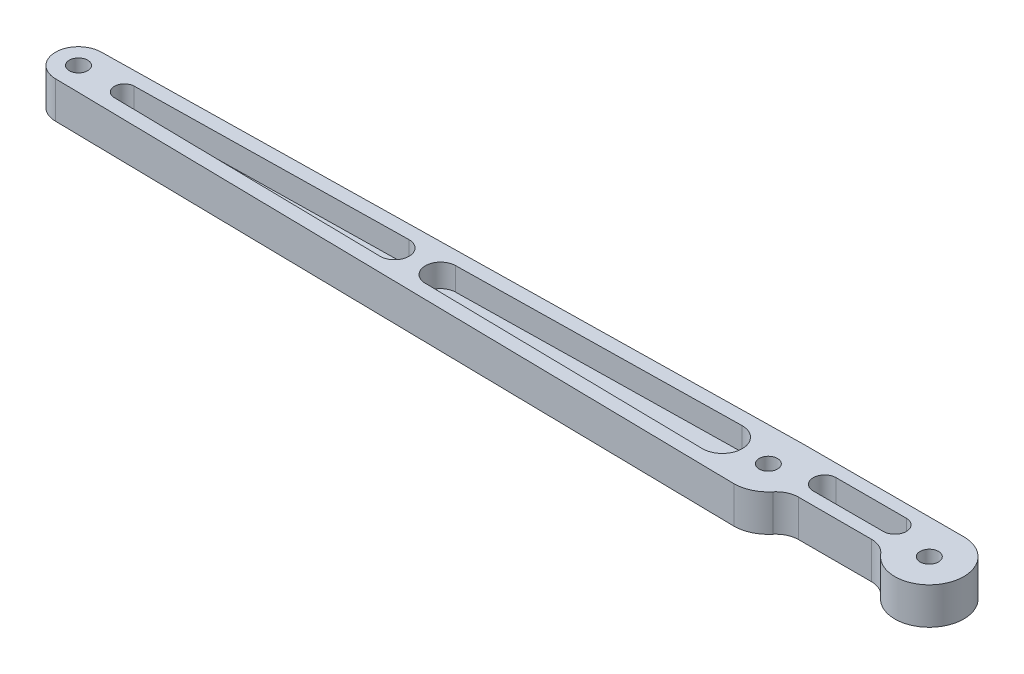
SolidWorks part; units mm, degrees
ref_plane "Front Plane" through (0, 0, 0) normal (0, 0, 1) x (1, 0, 0)
ref_plane "Top Plane" through (0, 0, 0) normal (0, 1, 0) x (1, 0, 0)
ref_plane "Right Plane" through (0, 0, 0) normal (1, 0, 0) x (0, 0, -1)
sketch "Sketch1" plane through (0, 0, 0) normal (0, 1, 0) x (1, 0, 0)
  line L0 (-68.657, 3.6299) -> (-61.657, 3.6299) construction
  line L1 (86.343, 11.1299) -> (121.343, 11.1299)
  line L5 (86.343, 11.1299) -> (86.343, -3.8701) construction
  line L6 (95.9477, 0.6299) -> (111.7383, 0.6299)
  line L7 (93.843, 3.6299) -> (128.843, 3.6299) construction
  line L8 (128.2168, 0.6299) -> (142.8276, 0.6299)
  line L9 (86.343, 11.1299) -> (-63.657, 8.6299)
  line L10 (86.343, -3.8701) -> (-63.657, -1.3701)
  line L11 (84.343, 3.6299) -> (88.343, 3.6299) construction
  circle A0 centre (86.343, 3.6299) radius 2
  circle A1 centre (121.343, 3.6299) radius 2
  arc A2 (121.343, -3.8701) -> (121.343, 11.1299) centre (121.343, 3.6299) ccw
  arc A3 (86.343, -3.8701) -> (92.1058, -1.1701) centre (86.343, 3.6299) ccw
  arc A4 (115.5802, -1.1701) -> (121.343, 11.1299) centre (121.343, 3.6299) ccw
  arc A5 (115.5802, -1.1701) -> (111.7383, 0.6299) centre (111.7383, -4.3701) ccw
  arc A6 (95.9477, 0.6299) -> (92.1058, -1.1701) centre (95.9477, -4.3701) ccw
  circle A7 centre (-63.657, 3.6299) radius 2
  arc A8 (-63.657, 8.6299) -> (-63.657, -1.3701) centre (-63.657, 3.6299) ccw
  dimension "D3" = 4
  dimension "D4" = 4
  dimension "D7" = 5
  dimension "D8" = 4
  dimension "D1" = 3
  dimension "D5" = 7.5
  dimension "D6" = 35
  dimension "D9" = 5
  dimension "D10" = 197.5
extrude "Boss-Extrude1" add sketch "Sketch1" along normal blind 8 contours L9 A8 L10 A3 A6 L6 A5 A4 A2 L1 A0 A1 A7
sketch "Sketch2" plane through (0, 8, 0) normal (0, 1, 0) x (1, 0, 0)
  line L0 (-53.657, 3.6299) -> (1.932, 3.6299) construction
  line L1 (-53.6931, 5.796) -> (5.0247, 6.7746)
  line L2 (-53.6931, 1.4639) -> (5.0247, 0.4853)
  line L3 (96.343, 5.8799) -> (93.4975, 5.8799) construction
  line L4 (96.343, 11.1299) -> (96.343, 0.6299) construction
  line L5 (86.343, 11.1299) -> (121.343, 11.1299) construction
  line L6 (95.9477, 0.6299) -> (111.7383, 0.6299) construction
  line L7 (111.5994, 11.1299) -> (111.5994, 0.6299) construction
  line L8 (96.343, 5.8799) -> (98.843, 5.8799) construction
  line L9 (111.5994, 5.8799) -> (114.1884, 5.8799) construction
  line L10 (96.343, 8.3799) -> (111.5994, 8.3799)
  line L11 (96.343, 3.3799) -> (111.5994, 3.3799)
  line L12 (18.3889, 3.6299) -> (76.343, 3.6299) construction
  line L13 (15.0219, 6.9413) -> (76.2708, 7.9621)
  line L14 (15.0219, 0.3186) -> (76.2708, -0.7022)
  arc A1 (-53.6931, 5.796) -> (-53.6931, 1.4639) centre (-53.657, 3.6299) ccw
  arc A2 (76.2708, -0.7022) -> (76.2708, 7.9621) centre (76.343, 3.6299) ccw
  arc A5 (96.343, 8.3799) -> (96.343, 3.3799) centre (96.343, 5.8799) ccw
  arc A7 (111.5994, 3.3799) -> (111.5994, 8.3799) centre (111.5994, 5.8799) ccw
  arc A8 (15.0219, 6.9413) -> (15.0219, 0.3186) centre (15.0771, 3.6299) ccw
  arc A9 (5.0247, 0.4853) -> (5.0247, 6.7746) centre (5.0771, 3.6299) ccw
  dimension "D1" = 5
  dimension "D2" = 5
  dimension "D3" = 10
extrude "Cut-Extrude1" cut sketch "Sketch2" against normal blind 5
